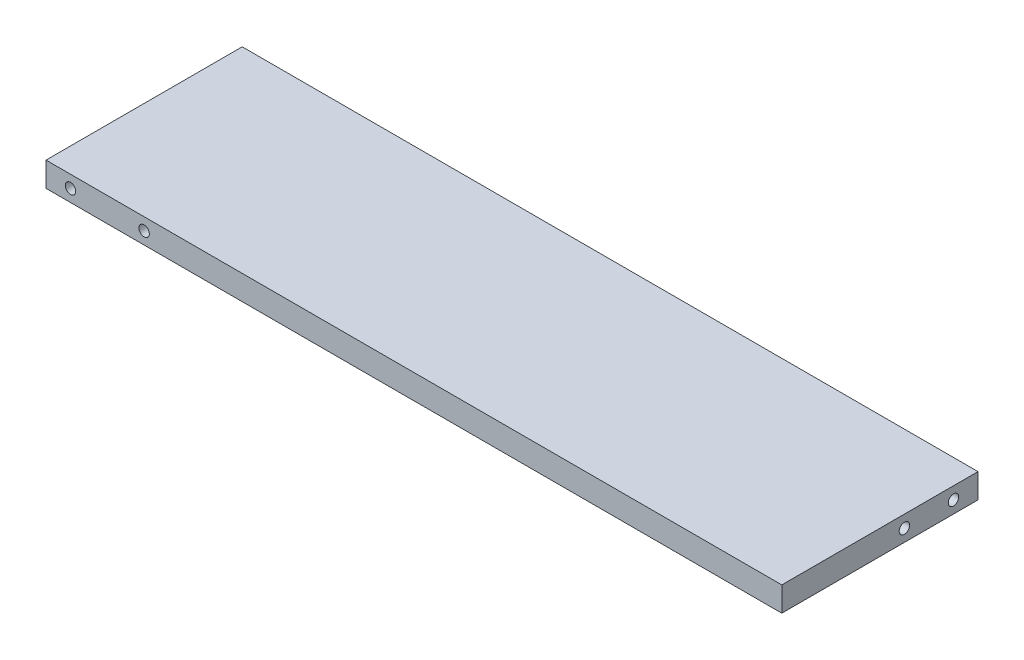
SolidWorks part; units mm, degrees
material "Acrylic (Medium-high impact)"
ref_plane "Front Plane" through (0, 0, 0) normal (0, 0, 1) x (1, 0, 0)
ref_plane "Top Plane" through (0, 0, 0) normal (0, 1, 0) x (1, 0, 0)
ref_plane "Right Plane" through (0, 0, 0) normal (1, 0, 0) x (0, 0, -1)
sketch "Sketch1" plane through (0, 0, 0) normal (0, 1, 0) x (1, 0, 0)
  line L1 (-95.25, -25.4) -> (95.25, -25.4)
  line L2 (-95.25, -25.4) -> (-95.25, 25.4)
  line L3 (-95.25, 25.4) -> (95.25, 25.4)
  line L4 (95.25, -25.4) -> (95.25, 25.4)
  line L5 (-95.25, -25.4) -> (95.25, 25.4) construction
  line L6 (-95.25, 25.4) -> (95.25, -25.4) construction
  point P0 (0, 0)
  dimension "D1" = 50.8
  dimension "D2" = 190.5
extrude "Boss-Extrude1" add sketch "Sketch1" along normal mid plane 6.35
sketch "Sketch2" plane through (0, 0, 25.4) normal (0, 0, 1) x (1, 0, 0)
  point P0 (-88.9, 0)
  point P1 (-69.85, 0)
hole_wizard "#6-32 Tapped Hole1" positions "Sketch3" profile "Sketch5" tap size "#6-32" standard "ANSI Inch"
sketch "Sketch3" plane through (0, 0, 25.4) normal (0, 0, 1) x (1, 0, 0)
  point P0 (-69.85, 0)
  point P3 (-88.9, 0)
cosmetic thread "Hole Thread1" parameters "D1"=50.8, "D2"=3.5052
cosmetic thread "Hole Thread2" parameters "D1"=50.8, "D2"=3.5052
sketch "Sketch5" plane through (-69.85, 0, 25.4) normal (1, 0, 0) x (0, -1, 0)
  line L0 (0, 0) -> (0, 13.5127)
  line L1 (0, 13.5127) -> (1.3525, 12.7)
  line L2 (1.3525, 12.7) -> (1.3525, 0)
  line L5 (1.3525, 0) -> (0, 0)
  line L10 (0, 13.5127) -> (-1.3525, 12.7) construction
  line L11 (0, -6.35) -> (0, 107.95) construction
  dimension "Tap Drill Dia." = 2.7051
  dimension "Tap Drill Depth" = 12.7
  dimension "Drill Angle" = 118
sketch "Sketch6" plane through (95.25, 0, 0) normal (1, 0, 0) x (0, 0, -1)
  point P0 (6.35, 0)
  point P1 (19.05, 0)
hole_wizard "#6-32 Tapped Hole2" positions "Sketch7" profile "Sketch8" tap size "#6-32" standard "ANSI Inch"
sketch "Sketch7" plane through (95.25, 0, 0) normal (1, 0, 0) x (0, 0, -1)
  point P0 (6.35, 0)
  point P3 (19.05, 0)
sketch "Sketch8" plane through (95.25, 0, -6.35) normal (0, 1, 0) x (0, 0, -1)
  line L0 (0, 0) -> (0, 15.0367)
  line L1 (0, 15.0367) -> (1.3525, 14.224)
  line L2 (1.3525, 14.224) -> (1.3525, 0)
  line L5 (1.3525, 0) -> (0, 0)
  line L10 (0, 15.0367) -> (-1.3526, 14.224) construction
  line L11 (0, -6.35) -> (0, 107.95) construction
  dimension "Tap Drill Dia." = 2.7051
  dimension "Tap Drill Depth" = 14.224
  dimension "Drill Angle" = 118
cosmetic thread "Hole Thread3" parameters "D1"=11.938, "D2"=3.5052
cosmetic thread "Hole Thread4" parameters "D1"=11.938, "D2"=3.5052
